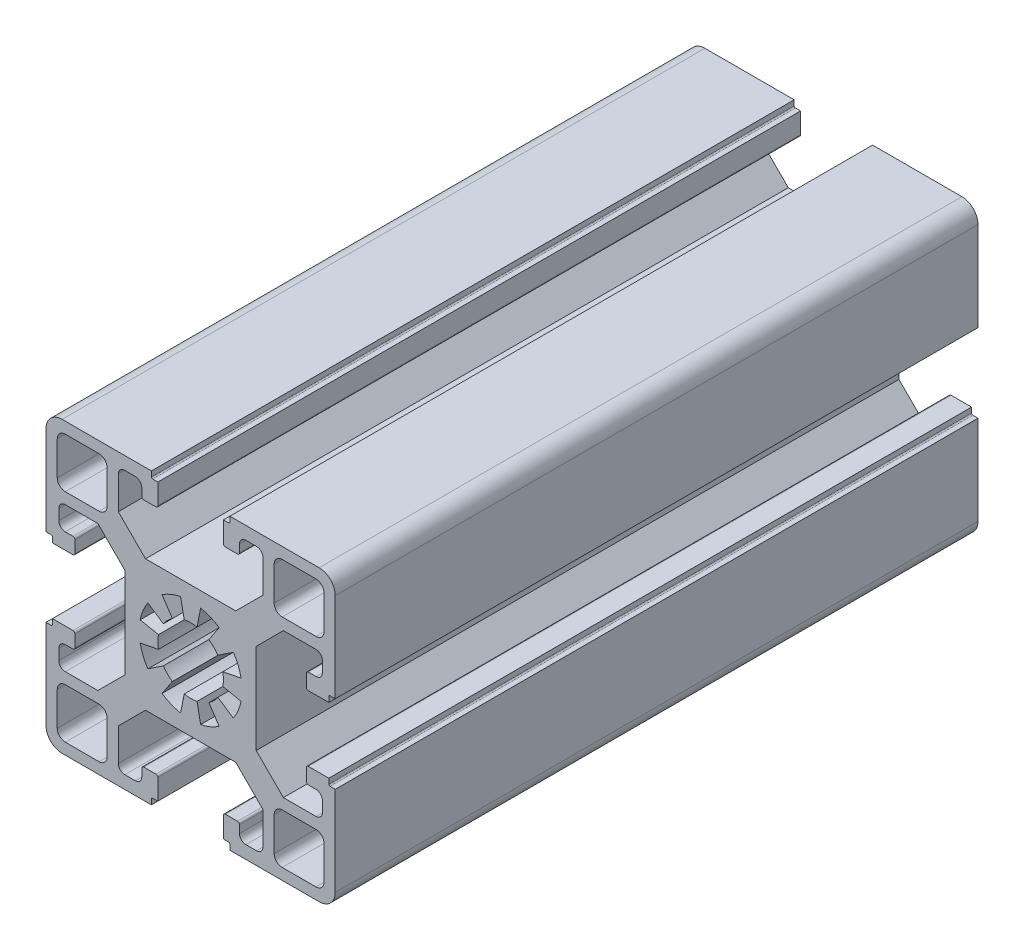
SolidWorks part; units mm, degrees
ref_plane "前视基准面" through (0, 0, 0) normal (0, 0, 1) x (1, 0, 0)
ref_plane "上视基准面" through (0, 0, 0) normal (0, 1, 0) x (1, 0, 0)
ref_plane "右视基准面" through (0, 0, 0) normal (1, 0, 0) x (0, 0, -1)
sketch "草图1" plane through (0, 0, 0) normal (0, 0, 1) x (1, 0, 0)
  line L0 (-7.794, 21.743) -> (-21.694, 21.743)
  line L1 (-24.194, 19.243) -> (-24.194, 5.343)
  line L2 (-6.794, 20.743) -> (-6.794, 17.543)
  line L3 (-7.094, 17.243) -> (-8.994, 17.243)
  line L4 (-9.294, 17.543) -> (-9.294, 18.743)
  line L5 (-10.294, 19.743) -> (-11.944, 19.743)
  line L6 (-12.944, 18.743) -> (-12.944, 13.675)
  line L7 (-21.194, 12.243) -> (-15.944, 12.243)
  line L8 (-14.694, 13.493) -> (-14.694, 18.743)
  line L9 (-15.944, 19.993) -> (-21.194, 19.993)
  line L10 (-22.444, 18.743) -> (-22.444, 13.493)
  line L11 (-16.126, 10.493) -> (-21.194, 10.493)
  line L12 (-22.194, 9.493) -> (-22.194, 7.843)
  line L13 (-21.194, 6.843) -> (-19.994, 6.843)
  line L14 (-19.694, 6.543) -> (-19.694, 4.643)
  line L15 (-19.994, 4.343) -> (-23.194, 4.343)
  line L16 (-6.794, 20.743) -> (-7.594, 20.743)
  line L17 (-7.794, 20.943) -> (-7.794, 21.743)
  line L18 (-24.194, 5.343) -> (-23.394, 5.343)
  line L19 (-23.194, 5.143) -> (-23.194, 4.343)
  line L20 (4.406, 21.743) -> (18.306, 21.743)
  line L21 (20.806, 19.243) -> (20.806, 5.343)
  line L22 (3.406, 20.743) -> (3.406, 17.543)
  line L23 (3.706, 17.243) -> (5.606, 17.243)
  line L24 (5.906, 17.543) -> (5.906, 18.743)
  line L25 (6.906, 19.743) -> (8.556, 19.743)
  line L26 (9.556, 18.743) -> (9.556, 13.675)
  line L27 (17.806, 12.243) -> (12.556, 12.243)
  line L28 (11.306, 13.493) -> (11.306, 18.743)
  line L29 (12.556, 19.993) -> (17.806, 19.993)
  line L30 (19.056, 18.743) -> (19.056, 13.493)
  line L31 (12.738, 10.493) -> (17.806, 10.493)
  line L32 (18.806, 9.493) -> (18.806, 7.843)
  line L33 (17.806, 6.843) -> (16.606, 6.843)
  line L34 (16.306, 6.543) -> (16.306, 4.643)
  line L35 (16.606, 4.343) -> (19.806, 4.343)
  line L36 (3.406, 20.743) -> (4.206, 20.743)
  line L37 (4.406, 20.943) -> (4.406, 21.743)
  line L38 (20.806, 5.343) -> (20.006, 5.343)
  line L39 (19.806, 5.143) -> (19.806, 4.343)
  line L40 (-7.794, -23.257) -> (-21.694, -23.257)
  line L41 (-24.194, -20.757) -> (-24.194, -6.857)
  line L42 (-6.794, -22.257) -> (-6.794, -19.057)
  line L43 (-7.094, -18.757) -> (-8.994, -18.757)
  line L44 (-9.294, -19.057) -> (-9.294, -20.257)
  line L45 (-10.294, -21.257) -> (-11.944, -21.257)
  line L46 (-12.944, -20.257) -> (-12.944, -15.189)
  line L47 (-21.194, -13.757) -> (-15.944, -13.757)
  line L48 (-14.694, -15.007) -> (-14.694, -20.257)
  line L49 (-15.944, -21.507) -> (-21.194, -21.507)
  line L50 (-22.444, -20.257) -> (-22.444, -15.007)
  line L51 (-16.126, -12.007) -> (-21.194, -12.007)
  line L52 (-22.194, -11.007) -> (-22.194, -9.357)
  line L53 (-21.194, -8.357) -> (-19.994, -8.357)
  line L54 (-19.694, -8.057) -> (-19.694, -6.157)
  line L55 (-19.994, -5.857) -> (-23.194, -5.857)
  line L56 (-6.794, -22.257) -> (-7.594, -22.257)
  line L57 (-7.794, -22.457) -> (-7.794, -23.257)
  line L58 (-24.194, -6.857) -> (-23.394, -6.857)
  line L59 (-23.194, -6.657) -> (-23.194, -5.857)
  line L60 (4.406, -23.257) -> (18.306, -23.257)
  line L61 (20.806, -20.757) -> (20.806, -6.857)
  line L62 (3.406, -22.257) -> (3.406, -19.057)
  line L63 (3.706, -18.757) -> (5.606, -18.757)
  line L64 (5.906, -19.057) -> (5.906, -20.257)
  line L65 (6.906, -21.257) -> (8.556, -21.257)
  line L66 (9.556, -20.257) -> (9.556, -15.189)
  line L67 (17.806, -13.757) -> (12.556, -13.757)
  line L68 (11.306, -15.007) -> (11.306, -20.257)
  line L69 (12.556, -21.507) -> (17.806, -21.507)
  line L70 (19.056, -20.257) -> (19.056, -15.007)
  line L71 (12.738, -12.007) -> (17.806, -12.007)
  line L72 (18.806, -11.007) -> (18.806, -9.357)
  line L73 (17.806, -8.357) -> (16.606, -8.357)
  line L74 (16.306, -8.057) -> (16.306, -6.157)
  line L75 (16.606, -5.857) -> (19.806, -5.857)
  line L76 (3.406, -22.257) -> (4.206, -22.257)
  line L77 (4.406, -22.457) -> (4.406, -23.257)
  line L78 (20.806, -6.857) -> (20.006, -6.857)
  line L79 (19.806, -6.657) -> (19.806, -5.857)
  line L80 (-6.1386, -7.4088) -> (-4.5274, -4.9975)
  line L81 (-3.2548, -8.6033) -> (-2.689, -5.759)
  line L82 (-0.1333, -8.6033) -> (-0.6991, -5.759)
  line L83 (2.7505, -7.4088) -> (1.1394, -4.9975)
  line L84 (4.9577, -5.2016) -> (2.5465, -3.5904)
  line L85 (6.1523, -2.3177) -> (3.308, -1.752)
  line L86 (6.1523, 0.8037) -> (3.308, 0.2379)
  line L87 (4.9577, 3.6875) -> (2.5465, 2.0764)
  line L88 (2.7505, 5.8947) -> (1.1394, 3.4835)
  line L89 (-0.1333, 7.0893) -> (-0.6991, 4.245)
  line L90 (-3.2548, 7.0893) -> (-2.689, 4.245)
  line L91 (-6.1386, 5.8947) -> (-4.5274, 3.4835)
  line L92 (-8.3458, 3.6875) -> (-5.9345, 2.0764)
  line L93 (-9.5403, 0.8037) -> (-6.696, 0.2379)
  line L94 (-9.5403, -2.3177) -> (-6.696, -1.752)
  line L95 (-8.3458, -5.2016) -> (-5.9345, -3.5904)
  line L96 (8.506, -7.775) -> (8.506, 6.261)
  line L97 (5.324, 9.443) -> (-8.712, 9.443)
  line L98 (-11.894, 6.261) -> (-11.894, -7.775)
  line L99 (-8.712, -10.957) -> (5.324, -10.957)
  line L100 (-12.944, 13.675) -> (-8.712, 9.443)
  line L101 (-16.126, 10.493) -> (-11.894, 6.261)
  line L102 (9.556, 13.675) -> (5.324, 9.443)
  line L103 (12.738, 10.493) -> (8.506, 6.261)
  line L104 (-12.944, -15.189) -> (-8.712, -10.957)
  line L105 (-16.126, -12.007) -> (-11.894, -7.775)
  line L106 (9.556, -15.189) -> (5.324, -10.957)
  line L107 (12.738, -12.007) -> (8.506, -7.775)
  arc A0 (-21.694, 21.743) -> (-24.194, 19.243) centre (-21.694, 19.243) ccw
  arc A1 (-7.094, 17.243) -> (-6.794, 17.543) centre (-7.094, 17.543) ccw
  arc A2 (-9.294, 17.543) -> (-8.994, 17.243) centre (-8.994, 17.543) ccw
  arc A3 (-9.294, 18.743) -> (-10.294, 19.743) centre (-10.294, 18.743) ccw
  arc A4 (-11.944, 19.743) -> (-12.944, 18.743) centre (-11.944, 18.743) ccw
  arc A5 (-15.944, 12.243) -> (-14.694, 13.493) centre (-15.944, 13.493) ccw
  arc A6 (-14.694, 18.743) -> (-15.944, 19.993) centre (-15.944, 18.743) ccw
  arc A7 (-21.194, 19.993) -> (-22.444, 18.743) centre (-21.194, 18.743) ccw
  arc A8 (-22.444, 13.493) -> (-21.194, 12.243) centre (-21.194, 13.493) ccw
  arc A9 (-21.194, 10.493) -> (-22.194, 9.493) centre (-21.194, 9.493) ccw
  arc A10 (-22.194, 7.843) -> (-21.194, 6.843) centre (-21.194, 7.843) ccw
  arc A11 (-19.694, 6.543) -> (-19.994, 6.843) centre (-19.994, 6.543) ccw
  arc A12 (-19.994, 4.343) -> (-19.694, 4.643) centre (-19.994, 4.643) ccw
  arc A13 (-7.794, 20.943) -> (-7.594, 20.743) centre (-7.594, 20.943) ccw
  arc A14 (-23.194, 5.143) -> (-23.394, 5.343) centre (-23.394, 5.143) ccw
  arc A15 (-2.689, -5.759) -> (-0.6991, -5.759) centre (-1.694, -0.757) ccw
  arc A16 (1.1394, -4.9975) -> (2.5465, -3.5904) centre (-1.694, -0.757) ccw
  arc A17 (3.308, -1.752) -> (3.308, 0.2379) centre (-1.694, -0.757) ccw
  arc A18 (2.5465, 2.0764) -> (1.1394, 3.4835) centre (-1.694, -0.757) ccw
  arc A19 (-0.6991, 4.245) -> (-2.689, 4.245) centre (-1.694, -0.757) ccw
  arc A20 (-4.5274, 3.4835) -> (-5.9345, 2.0764) centre (-1.694, -0.757) ccw
  arc A21 (-6.696, 0.2379) -> (-6.696, -1.752) centre (-1.694, -0.757) ccw
  arc A22 (-5.9345, -3.5904) -> (-4.5274, -4.9975) centre (-1.694, -0.757) ccw
  arc A23 (-6.1386, -7.4088) -> (-3.2548, -8.6033) centre (-1.694, -0.757) ccw
  arc A24 (-0.1333, -8.6033) -> (2.7505, -7.4088) centre (-1.694, -0.757) ccw
  arc A25 (4.9577, -5.2016) -> (6.1523, -2.3177) centre (-1.694, -0.757) ccw
  arc A26 (6.1523, 0.8037) -> (4.9577, 3.6875) centre (-1.694, -0.757) ccw
  arc A27 (2.7505, 5.8947) -> (-0.1333, 7.0893) centre (-1.694, -0.757) ccw
  arc A28 (-3.2548, 7.0893) -> (-6.1386, 5.8947) centre (-1.694, -0.757) ccw
  arc A29 (-8.3458, 3.6875) -> (-9.5403, 0.8037) centre (-1.694, -0.757) ccw
  arc A30 (-9.5403, -2.3177) -> (-8.3458, -5.2016) centre (-1.694, -0.757) ccw
  arc A31 (20.806, 19.243) -> (18.306, 21.743) centre (18.306, 19.243) ccw
  arc A32 (3.406, 17.543) -> (3.706, 17.243) centre (3.706, 17.543) ccw
  arc A33 (5.606, 17.243) -> (5.906, 17.543) centre (5.606, 17.543) ccw
  arc A34 (6.906, 19.743) -> (5.906, 18.743) centre (6.906, 18.743) ccw
  arc A35 (9.556, 18.743) -> (8.556, 19.743) centre (8.556, 18.743) ccw
  arc A36 (11.306, 13.493) -> (12.556, 12.243) centre (12.556, 13.493) ccw
  arc A37 (12.556, 19.993) -> (11.306, 18.743) centre (12.556, 18.743) ccw
  arc A38 (19.056, 18.743) -> (17.806, 19.993) centre (17.806, 18.743) ccw
  arc A39 (17.806, 12.243) -> (19.056, 13.493) centre (17.806, 13.493) ccw
  arc A40 (18.806, 9.493) -> (17.806, 10.493) centre (17.806, 9.493) ccw
  arc A41 (17.806, 6.843) -> (18.806, 7.843) centre (17.806, 7.843) ccw
  arc A42 (16.606, 6.843) -> (16.306, 6.543) centre (16.606, 6.543) ccw
  arc A43 (16.306, 4.643) -> (16.606, 4.343) centre (16.606, 4.643) ccw
  arc A44 (4.206, 20.743) -> (4.406, 20.943) centre (4.206, 20.943) ccw
  arc A45 (20.006, 5.343) -> (19.806, 5.143) centre (20.006, 5.143) ccw
  arc A46 (-24.194, -20.757) -> (-21.694, -23.257) centre (-21.694, -20.757) ccw
  arc A47 (-6.794, -19.057) -> (-7.094, -18.757) centre (-7.094, -19.057) ccw
  arc A48 (-8.994, -18.757) -> (-9.294, -19.057) centre (-8.994, -19.057) ccw
  arc A49 (-10.294, -21.257) -> (-9.294, -20.257) centre (-10.294, -20.257) ccw
  arc A50 (-12.944, -20.257) -> (-11.944, -21.257) centre (-11.944, -20.257) ccw
  arc A51 (-14.694, -15.007) -> (-15.944, -13.757) centre (-15.944, -15.007) ccw
  arc A52 (-15.944, -21.507) -> (-14.694, -20.257) centre (-15.944, -20.257) ccw
  arc A53 (-22.444, -20.257) -> (-21.194, -21.507) centre (-21.194, -20.257) ccw
  arc A54 (-21.194, -13.757) -> (-22.444, -15.007) centre (-21.194, -15.007) ccw
  arc A55 (-22.194, -11.007) -> (-21.194, -12.007) centre (-21.194, -11.007) ccw
  arc A56 (-21.194, -8.357) -> (-22.194, -9.357) centre (-21.194, -9.357) ccw
  arc A57 (-19.994, -8.357) -> (-19.694, -8.057) centre (-19.994, -8.057) ccw
  arc A58 (-19.694, -6.157) -> (-19.994, -5.857) centre (-19.994, -6.157) ccw
  arc A59 (-7.594, -22.257) -> (-7.794, -22.457) centre (-7.594, -22.457) ccw
  arc A60 (-23.394, -6.857) -> (-23.194, -6.657) centre (-23.394, -6.657) ccw
  arc A61 (18.306, -23.257) -> (20.806, -20.757) centre (18.306, -20.757) ccw
  arc A62 (3.706, -18.757) -> (3.406, -19.057) centre (3.706, -19.057) ccw
  arc A63 (5.906, -19.057) -> (5.606, -18.757) centre (5.606, -19.057) ccw
  arc A64 (5.906, -20.257) -> (6.906, -21.257) centre (6.906, -20.257) ccw
  arc A65 (8.556, -21.257) -> (9.556, -20.257) centre (8.556, -20.257) ccw
  arc A66 (12.556, -13.757) -> (11.306, -15.007) centre (12.556, -15.007) ccw
  arc A67 (11.306, -20.257) -> (12.556, -21.507) centre (12.556, -20.257) ccw
  arc A68 (17.806, -21.507) -> (19.056, -20.257) centre (17.806, -20.257) ccw
  arc A69 (19.056, -15.007) -> (17.806, -13.757) centre (17.806, -15.007) ccw
  arc A70 (17.806, -12.007) -> (18.806, -11.007) centre (17.806, -11.007) ccw
  arc A71 (18.806, -9.357) -> (17.806, -8.357) centre (17.806, -9.357) ccw
  arc A72 (16.306, -8.057) -> (16.606, -8.357) centre (16.606, -8.057) ccw
  arc A73 (16.606, -5.857) -> (16.306, -6.157) centre (16.606, -6.157) ccw
  arc A74 (4.406, -22.457) -> (4.206, -22.257) centre (4.206, -22.457) ccw
  arc A75 (19.806, -6.657) -> (20.006, -6.857) centre (20.006, -6.657) ccw
extrude "凸台-拉伸1" add sketch "草图1" along normal blind 100
